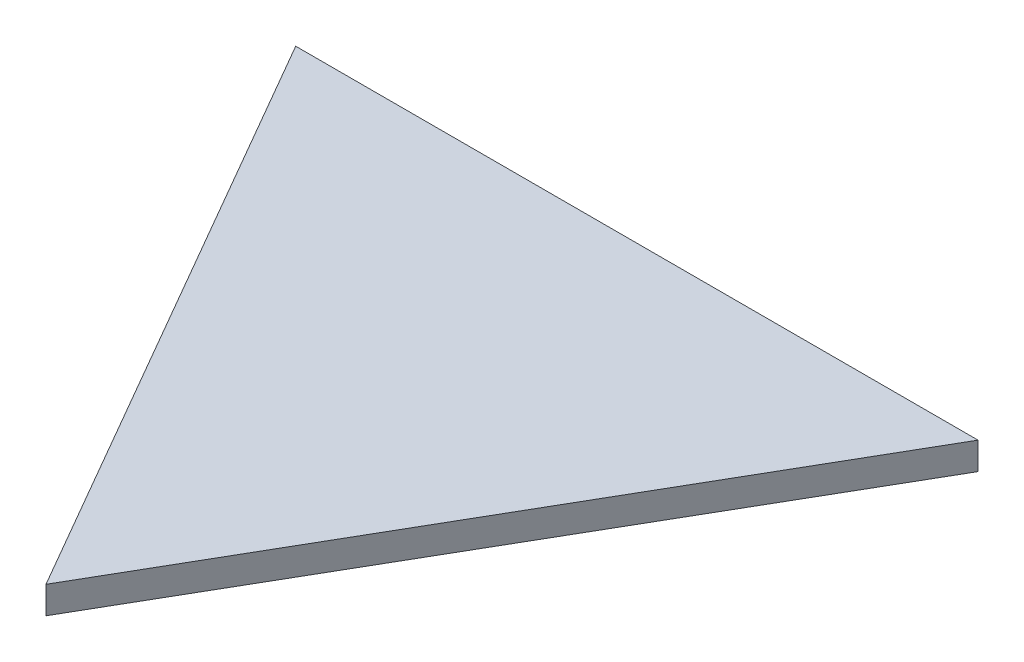
SolidWorks part; units mm, degrees
ref_plane "Front Plane" through (0, 0, 0) normal (0, 0, 1) x (1, 0, 0)
ref_plane "Top Plane" through (0, 0, 0) normal (0, 1, 0) x (1, 0, 0)
ref_plane "Right Plane" through (0, 0, 0) normal (1, 0, 0) x (0, 0, -1)
sketch "Sketch1" plane through (0, 0, 0) normal (0, 1, 0) x (1, 0, 0)
  line L0 (-125, 72.16) -> (0, -144.34)
  line L1 (-125, 72.16) -> (125, 72.16)
  line L2 (-125, 72.16) -> (-125, -144.34)
  line L3 (-125, -144.34) -> (125, -144.34)
  line L4 (125, 72.16) -> (125, -144.34)
  line L5 (0, -144.34) -> (125, 72.16)
  dimension "D1" = 216.5
  dimension "D2" = 250
  dimension "D3" = 125
  dimension "D4" = 72.16
  dimension "D5" = 125
extrude "Extrude1" add sketch "Sketch1" along normal blind 10 contours L0 L5 L1
